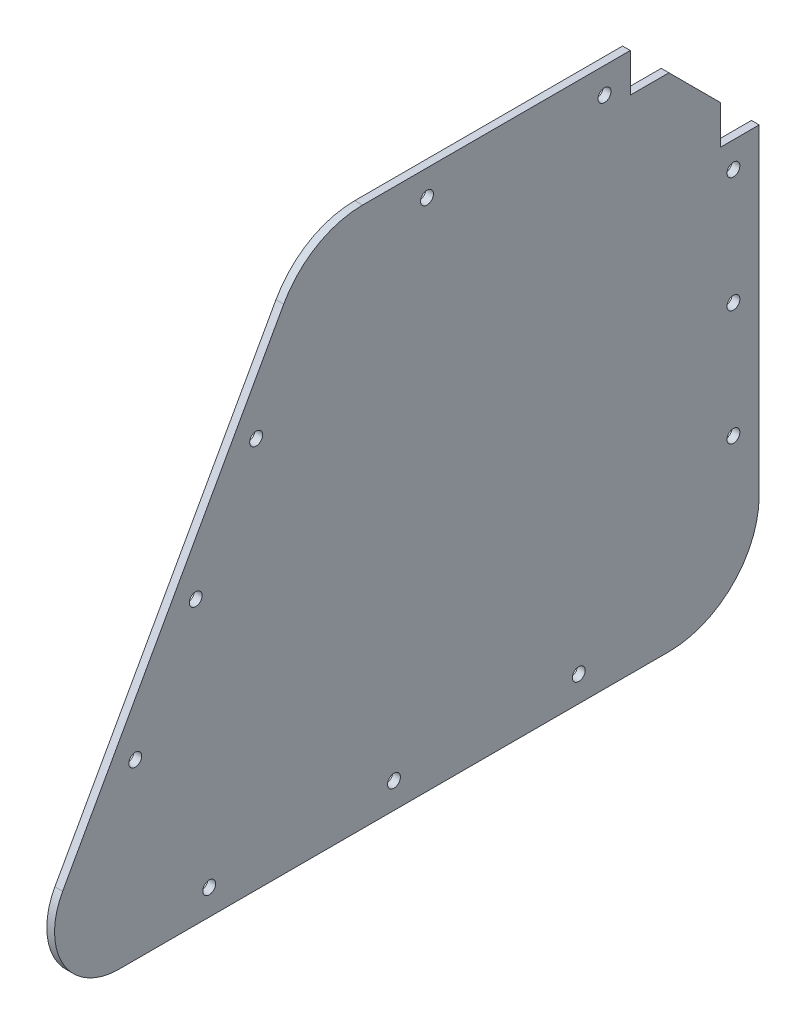
SolidWorks part; units mm, degrees
material "Acrylic (Medium-high impact)"
ref_plane "Front Plane" through (0, 0, 0) normal (0, 0, 1) x (1, 0, 0)
ref_plane "Top Plane" through (0, 0, 0) normal (0, 1, 0) x (1, 0, 0)
ref_plane "Right Plane" through (0, 0, 0) normal (1, 0, 0) x (0, 0, -1)
sketch "Sketch1" plane through (0, 0, 0) normal (1, 0, 0) x (0, 0, -1)
  line L0 (0, -1000) -> (0, 49000) construction
  line L1 (-1000, 0) -> (49000, 0) construction
  line L14 (-12.1885, 179.5) -> (106.6837, 179.5) construction
  line L15 (-29.6717, 169.2129) -> (-115.4252, 14.8564) construction
  line L16 (-106.6837, 0) -> (106.6837, 0) construction
  line L17 (126.6837, 20) -> (126.6837, 159.5) construction
  line L18 (-12.1885, 194.5) -> (106.6837, 194.5)
  line L19 (141.6837, 20) -> (141.6837, 159.5)
  line L20 (-106.6837, -15) -> (106.6837, -15)
  line L21 (-42.784, 176.4975) -> (-128.5376, 22.1411)
  arc A12 (-106.6837, 0) -> (-115.4252, 14.8564) centre (-106.6837, 10) cw construction
  arc A13 (106.6837, 0) -> (126.6837, 20) centre (106.6837, 20) ccw construction
  arc A14 (126.6837, 159.5) -> (106.6837, 179.5) centre (106.6837, 159.5) ccw construction
  arc A16 (-29.6717, 169.2129) -> (-12.1885, 179.5) centre (-12.1885, 159.5) cw construction
  arc A17 (141.6837, 159.5) -> (106.6837, 194.5) centre (106.6837, 159.5) ccw
  arc A18 (106.6837, -15) -> (141.6837, 20) centre (106.6837, 20) ccw
  arc A19 (-106.6837, -15) -> (-128.5376, 22.1411) centre (-106.6837, 10) cw
  arc A20 (-42.784, 176.4975) -> (-12.1885, 194.5) centre (-12.1885, 159.5) cw
  point P17 (47.2476, 179.5)
  point P18 (0, 0)
  dimension "D2" = 20
  dimension "D3" = 20
  dimension "D5" = 79.4361
  dimension "D1" = 10
  dimension "D4" = 20
  dimension "D6" = 213.3673
  dimension "D7" = 179.5
  dimension "D8" = 15
extrude "Boss-Extrude1" add sketch "Sketch1" along normal blind 3
sketch "Sketch2" plane through (3, 0, 0) normal (1, 0, 0) x (0, 0, -1)
  line L4 (-34.0424, 171.6411) -> (-119.796, 17.2846)
  line L5 (-34.0424, 171.6411) -> (-119.796, 17.2846) construction
  line L6 (-106.6837, -5) -> (106.6837, -5)
  line L7 (-106.6837, -5) -> (106.6837, -5) construction
  line L8 (131.6837, 20) -> (131.6837, 159.5)
  line L9 (131.6837, 20) -> (131.6837, 159.5) construction
  line L10 (106.6837, 184.5) -> (-12.1885, 184.5)
  line L11 (106.6837, 184.5) -> (-12.1885, 184.5) construction
  arc A4 (-12.1885, 184.5) -> (-34.0424, 171.6411) centre (-12.1885, 159.5) ccw
  arc A5 (-12.1885, 184.5) -> (-34.0424, 171.6411) centre (-12.1885, 159.5) ccw construction
  arc A6 (-119.796, 17.2846) -> (-106.6837, -5) centre (-106.6837, 10) ccw
  arc A7 (-119.796, 17.2846) -> (-106.6837, -5) centre (-106.6837, 10) ccw construction
  arc A8 (106.6837, -5) -> (131.6837, 20) centre (106.6837, 20) ccw
  arc A9 (106.6837, -5) -> (131.6837, 20) centre (106.6837, 20) ccw construction
  arc A10 (131.6837, 159.5) -> (106.6837, 184.5) centre (106.6837, 159.5) ccw
  arc A11 (131.6837, 159.5) -> (106.6837, 184.5) centre (106.6837, 159.5) ccw construction
  circle A32 centre (81.6837, 184.5) radius 2.5
  circle A33 centre (12.8115, 184.5) radius 2.5
  circle A34 centre (131.6837, 134.5) radius 2.5
  circle A35 centre (131.6837, 89.75) radius 2.5
  circle A44 centre (131.6837, 44.9999) radius 2.5
  circle A45 centre (71.6837, -5) radius 2.5
  circle A46 centre (0, -5) radius 2.5
  circle A47 centre (-71.6837, -5) radius 2.5
  circle A48 centre (-100.3703, 52.2509) radius 2.5
  circle A49 centre (-76.9192, 94.4629) radius 2.5
  circle A50 centre (-53.4682, 136.6748) radius 2.5
  dimension "D4" = 25
  dimension "D6" = 24.9999
  dimension "D7" = 35
  dimension "D8" = 35
  dimension "D9" = 40
  dimension "D10" = 40
  dimension "D2" = 5
  dimension "D5" = 25
  dimension "D3" = 25
  dimension "D1" = 10
extrude "Cut-Extrude1" cut sketch "Sketch2" against normal up to next
sketch "Sketch4" plane through (3, 0, 0) normal (1, 0, 0) x (0, 0, -1)
  line L0 (141.6837, 20) -> (141.6837, 159.5) construction
  line L1 (141.6837, 144.5) -> (126.6837, 144.5)
  line L2 (141.6837, 144.5) -> (141.6837, 194.5)
  line L3 (141.6837, 194.5) -> (91.6837, 194.5)
  line L4 (91.6837, 179.5) -> (91.6837, 194.5)
  line L5 (106.6837, 194.5) -> (-12.1885, 194.5) construction
  line L6 (126.6837, 144.5) -> (126.6837, 159.5)
  line L7 (91.6837, 179.5) -> (106.6837, 179.5)
  arc A0 (126.6837, 159.5) -> (106.6837, 179.5) centre (106.6837, 159.5) ccw
  dimension "D5" = 20
  dimension "D1" = 50
  dimension "D2" = 50
  dimension "D3" = 15
  dimension "D4" = 15
extrude "Cut-Extrude2" cut sketch "Sketch4" against normal up to next
sketch "Sketch5" plane through (3, 0, 0) normal (1, 0, 0) x (0, 0, -1)
  line L0 (106.6837, 179.5) -> (126.6837, 159.5)
  arc A0 (126.6837, 159.5) -> (106.6837, 179.5) centre (106.6837, 159.5) ccw construction
  arc A1 (126.6837, 159.5) -> (106.6837, 179.5) centre (106.6837, 159.5) ccw
extrude "Cut-Extrude3" cut sketch "Sketch5" against normal up to next
